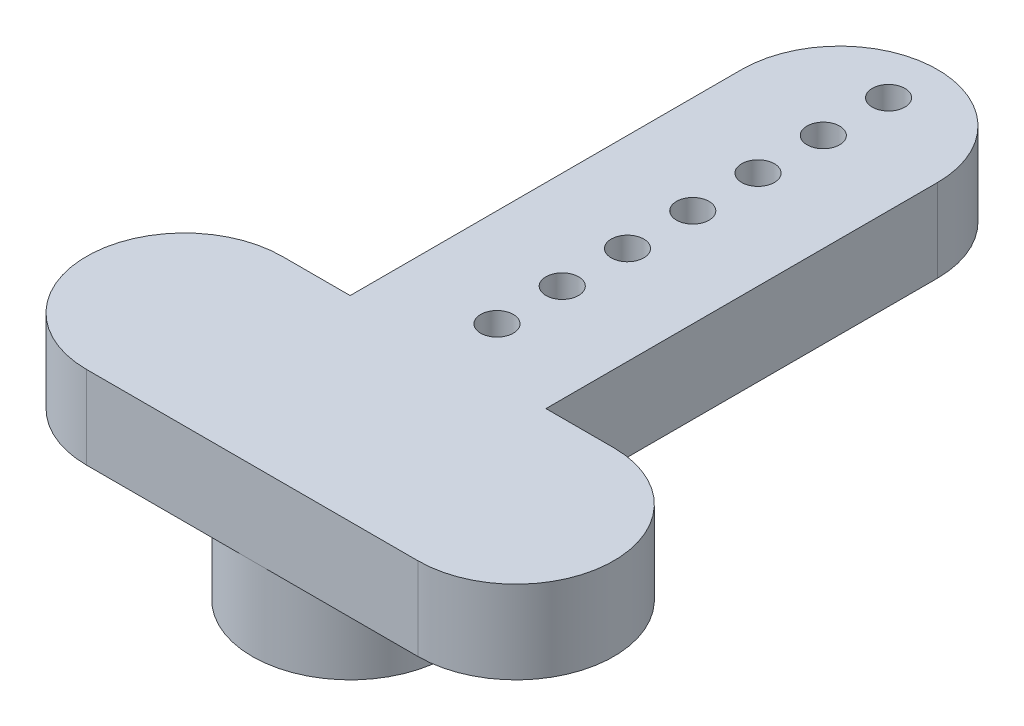
SolidWorks part; units mm, degrees
ref_plane "Front" through (0, 0, 0) normal (0, 0, 1) x (1, 0, 0)
ref_plane "Top" through (0, 0, 0) normal (0, 1, 0) x (1, 0, 0)
ref_plane "Right" through (0, 0, 0) normal (1, 0, 0) x (0, 0, -1)
sketch "Sketch1" plane through (0, 0, 0) normal (0, 1, 0) x (1, 0, 0)
  circle A0 centre (0, 0) radius 3
  dimension "D1" = 6
extrude "Boss-Extrude1" add sketch "Sketch1" along normal blind 2.54
sketch "Sketch2" plane through (0, 2.54, 0) normal (0, 1, 0) x (1, 0, 0)
  line L0 (0, -1.397) -> (0, 1.397) construction
  line L1 (-5.08, 3) -> (5.08, 3)
  line L2 (-5.08, 3) -> (-5.08, -3)
  line L3 (-5.08, -3) -> (5.08, -3)
  line L4 (5.08, 3) -> (5.08, -3)
  line L5 (-5.08, 3) -> (5.08, -3) construction
  line L6 (-5.08, -3) -> (5.08, 3) construction
  line L7 (-1.397, 0) -> (1.397, 0) construction
  line L8 (-3, -15) -> (3, -15)
  line L9 (-3, -15) -> (-3, 15)
  line L10 (-3, 15) -> (3, 15)
  line L11 (3, -15) -> (3, 15)
  line L12 (-3, -15) -> (3, 15) construction
  line L13 (-3, 15) -> (3, -15) construction
  line L14 (-3, -3.6406) -> (3, -3.6406)
  circle A0 centre (0, 0) radius 3 construction
  arc A1 (-5.08, 3) -> (-5.08, -3) centre (-5.08, 0) ccw
  arc A2 (5.08, 3) -> (5.08, -3) centre (5.08, 0) cw
  arc A3 (-3, 15) -> (3, 15) centre (0, 15) cw
  arc A4 (-3, -15) -> (3, -15) centre (0, -15) ccw
  point P0 (0, 0)
  point P12 (0, 0)
  circle M9 centre (0, 0) radius 3
  dimension "D2" = 15
  dimension "D1" = 10.16
extrude "Boss-Extrude2" add sketch "Sketch2" along normal blind 2.54 contours A3 L10 | L1 L11 L10 L9 | L2 A1 | L3 L9 L1 L2 | L11 L1 M9 | M9 | L3 L11 M9 | A2 L4 | L11 L3 L4 L1 | L9 L3 M9 | L9 L1 M9
sketch "Sketch3" plane through (0, 5.08, 0) normal (0, 1, 0) x (1, 0, 0)
  line L0 (0, -2.794) -> (0, 2.794) construction
  circle A0 centre (0, 16.5) radius 0.5
  arc A1 (3, 15) -> (-3, 15) centre (0, 15) ccw construction
  circle A2 centre (0, 14.5) radius 0.5
  circle A3 centre (0, 12.5) radius 0.5
  circle A4 centre (0, 10.5) radius 0.5
  circle A5 centre (0, 8.5) radius 0.5
  circle A6 centre (0, 6.5) radius 0.5
  circle A7 centre (0, 4.5) radius 0.5
  dimension "D2" = 1
  dimension "D1" = 1.5
  dimension "D3" = 7
extrude "Cut-Extrude1" cut sketch "Sketch3" against normal blind 10
